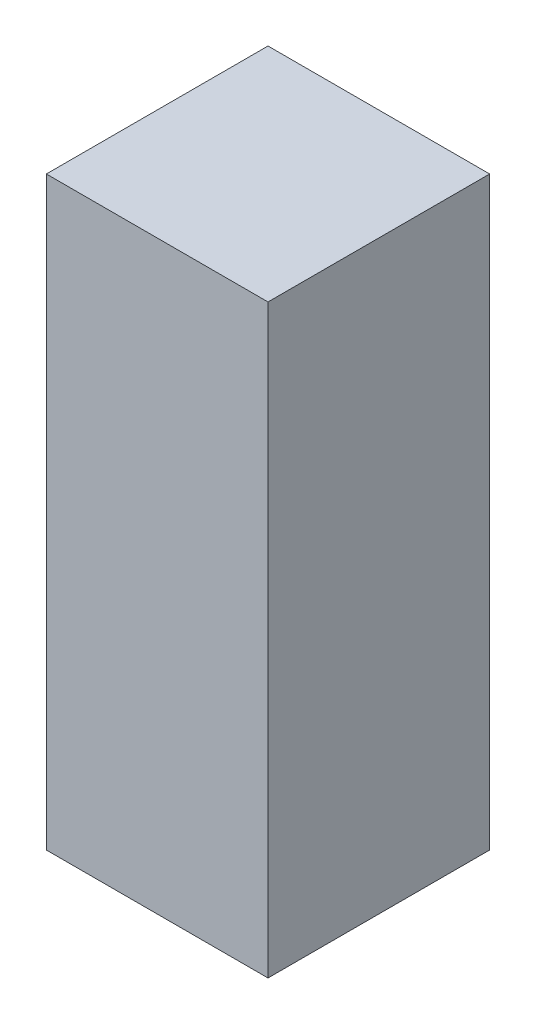
SolidWorks part; units mm, degrees
ref_plane "Front Plane" through (0, 0, 0) normal (0, 0, 1) x (1, 0, 0)
ref_plane "Top Plane" through (0, 0, 0) normal (0, 1, 0) x (1, 0, 0)
ref_plane "Right Plane" through (0, 0, 0) normal (1, 0, 0) x (0, 0, -1)
sketch "Sketch1" plane through (0, 0, 0) normal (0, 1, 0) x (1, 0, 0)
  line L1 (-2.65, 2.65) -> (2.65, 2.65)
  line L2 (-2.65, 2.65) -> (-2.65, -2.65)
  line L3 (-2.65, -2.65) -> (2.65, -2.65)
  line L4 (2.65, 2.65) -> (2.65, -2.65)
  line L5 (-2.65, 2.65) -> (2.65, -2.65) construction
  line L6 (-2.65, -2.65) -> (2.65, 2.65) construction
  point P0 (0, 0)
  dimension "D1" = 5.3
  dimension "D2" = 5.3
extrude "Boss-Extrude1" add sketch "Sketch1" along normal blind 14
